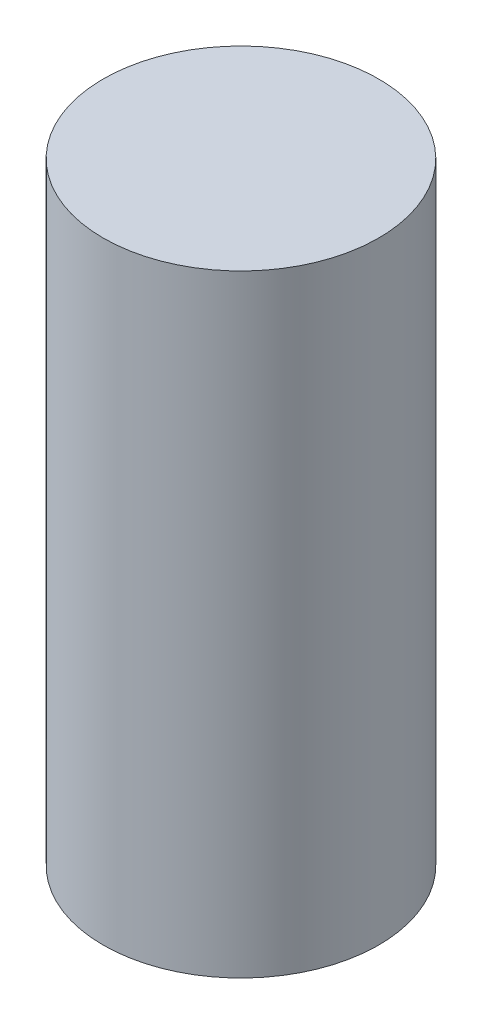
SolidWorks part; units mm, degrees
ref_plane "Front Plane" through (0, 0, 0) normal (0, 0, 1) x (1, 0, 0)
ref_plane "Top Plane" through (0, 0, 0) normal (0, 1, 0) x (1, 0, 0)
ref_plane "Right Plane" through (0, 0, 0) normal (1, 0, 0) x (0, 0, -1)
sketch "Sketch1" plane through (0, 0, 0) normal (0, 1, 0) x (1, 0, 0)
  circle A0 centre (0, 0) radius 2.475
  dimension "D1" = 4.95
extrude "Boss-Extrude1" add sketch "Sketch1" along normal blind 11
